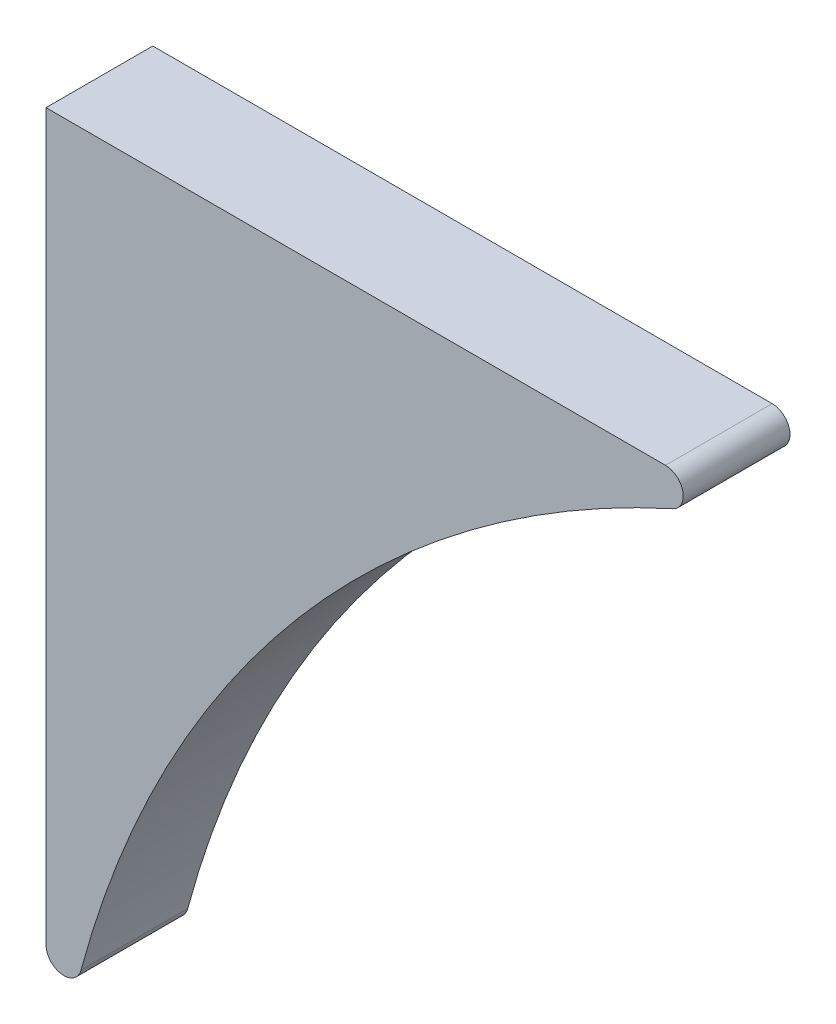
SolidWorks part; units mm, degrees
material "Plain Carbon Steel"
ref_plane "Front Plane" through (0, 0, 0) normal (0, 0, 1) x (1, 0, 0)
ref_plane "Top Plane" through (0, 0, 0) normal (0, 1, 0) x (1, 0, 0)
ref_plane "Right Plane" through (0, 0, 0) normal (1, 0, 0) x (0, 0, -1)
sketch "Sketch1" plane through (0, 0, 0) normal (0, 0, 1) x (1, 0, 0)
  line L0 (0, 0) -> (0, -60)
  line L1 (0, -55) -> (0, 55) construction
  line L2 (0, -60) -> (40, 0)
  line L3 (55, 0) -> (-55, 0) construction
  line L4 (40, 0) -> (0, 0)
  dimension "D1" = 60
  dimension "D2" = 40
extrude "Boss-Extrude1" add sketch "Sketch1" along normal mid plane 6
sketch "Sketch2" plane through (0, 0, 0) normal (0, 0, 1) x (1, 0, 0)
  line L0 (40, 0) -> (0, -60)
  arc A0 (0, -60) -> (40, 0) centre (59.9037, -56.6025) cw
  dimension "D1" = 60
extrude "Cut-Extrude1" cut sketch "Sketch2" against normal through all both and the other way through all
fillet "Fillet1" radius 1 2 edges at (0, -53.205, 0) (40, 0, 0)
